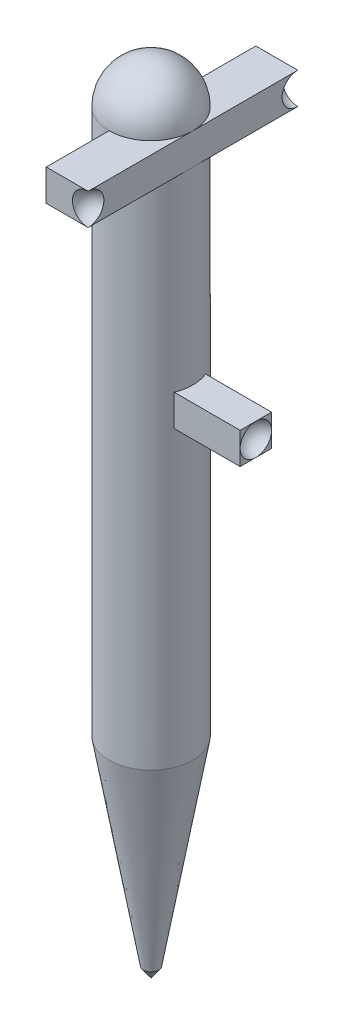
SolidWorks part; units mm, degrees
ref_plane "Front Plane" through (0, 0, 0) normal (0, 0, 1) x (1, 0, 0)
ref_plane "Top Plane" through (0, 0, 0) normal (0, 1, 0) x (1, 0, 0)
ref_plane "Right Plane" through (0, 0, 0) normal (1, 0, 0) x (0, 0, -1)
sketch "Sketch1" plane through (0, 0, 0) normal (0, 0, 1) x (1, 0, 0)
  line L0 (50.8, 0) -> (50.8, -660.4)
  line L1 (50.8, -660.4) -> (9.1208, -901.7)
  line L2 (9.1208, -901.7) -> (0, -914.4)
  line L3 (0, -914.4) -> (0, 50.8)
  arc A0 (0, 50.8) -> (50.8, 0) centre (0, 0) cw
  dimension "D1" = 914.4
  dimension "D2" = 50.8
  dimension "D3" = 254
  dimension "D4" = 12.7
revolve "Revolve1" add sketch "Sketch1" angle 360 about L3
sketch "Sketch4" plane through (0, 0, 0) normal (0, 0, 1) x (1, 0, 0)
  line L1 (0, 0) -> (50.8, 0)
  line L2 (0, 0) -> (0, -38.1)
  line L3 (0, -38.1) -> (50.8, -38.1)
  line L4 (50.8, 0) -> (50.8, -38.1)
  dimension "D1" = 38.1
  dimension "D2" = 50.8
extrude "Boss-Extrude3" add sketch "Sketch4" along normal mid plane 254
sketch "Sketch2" plane through (0, 0, 0) normal (0, 0, 1) x (1, 0, 0)
  line L4 (0, -266.7) -> (0, -304.8)
  line L5 (0, -304.8) -> (127, -304.8)
  line L7 (127, -266.7) -> (0, -266.7)
  line L8 (127, -266.7) -> (127, -304.8)
  point P0 (127, -285.75)
  dimension "D1" = 38.1
  dimension "D2" = 127
  dimension "D3" = 285.75
extrude "Boss-Extrude2" add sketch "Sketch2" along normal mid plane 38.1
sketch "Sketch5" plane through (0, 0, 127) normal (0, 0, 1) x (1, 0, 0)
  line L0 (50.8, -38.1) -> (50.8, 0) construction
  line L1 (50.8, 0) -> (50.8, -38.1)
  arc A0 (50.8, 0) -> (50.8, -38.1) centre (50.8, -19.05) ccw
revolve "Cut-Revolve1" cut sketch "Sketch5" angle 360 about L1
mirror "Mirror1" about plane through (0, 0, 0) normal (0, 0, 1) of "Cut-Revolve1"
sketch "Sketch6" plane through (0, 0, 0) normal (0, 0, 1) x (1, 0, 0)
  line L1 (127, -304.8) -> (127, -266.7) construction
  line L2 (127, -266.7) -> (127, -304.8)
  arc A0 (127, -266.7) -> (127, -304.8) centre (127, -285.75) ccw
revolve "Cut-Revolve2" cut sketch "Sketch6" angle 360 about L2
